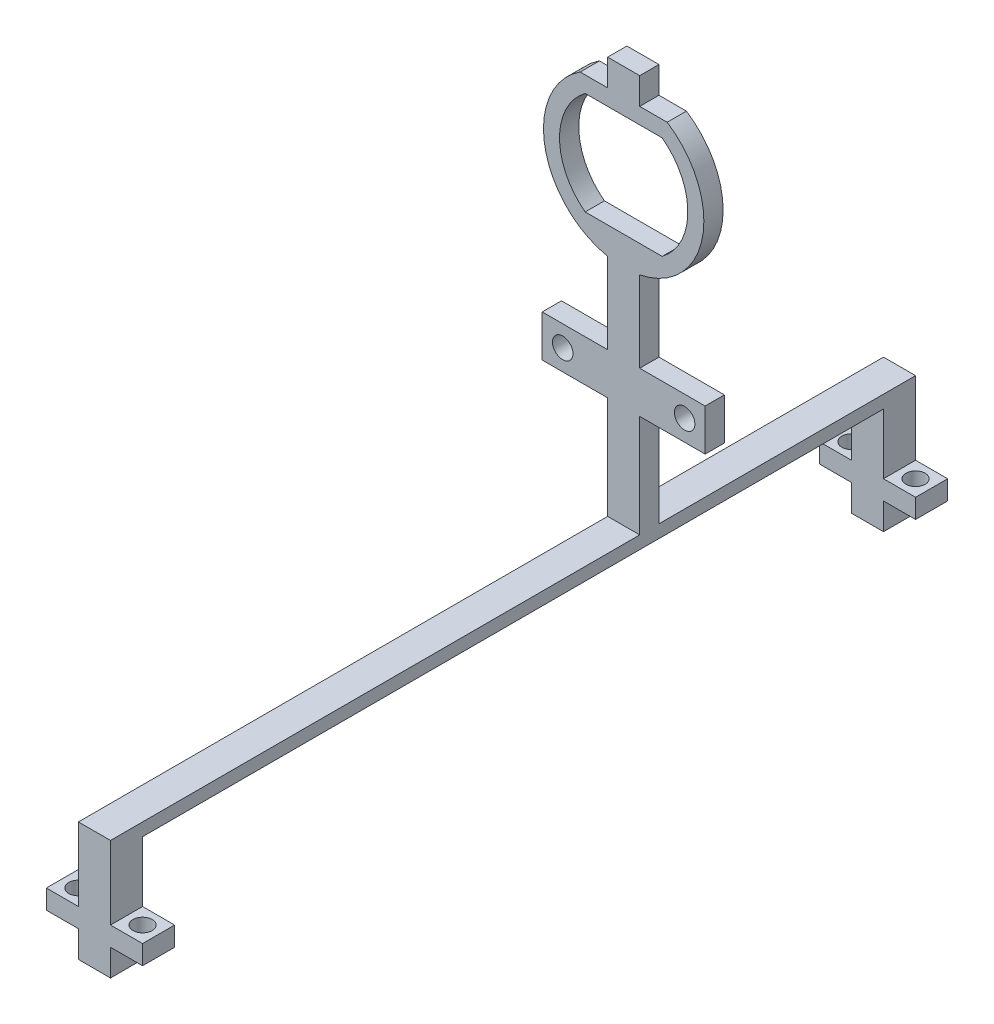
SolidWorks part; units mm, degrees
ref_plane "Front Plane" through (0, 0, 0) normal (0, 0, 1) x (1, 0, 0)
ref_plane "Top Plane" through (0, 0, 0) normal (0, 1, 0) x (1, 0, 0)
ref_plane "Right Plane" through (0, 0, 0) normal (1, 0, 0) x (0, 0, -1)
sketch "Sketch1" plane through (0, 0, 0) normal (0, 0, 1) x (1, 0, 0)
  line L5 (-18.4746, 0) -> (14.4817, 0) construction
  line L8 (0, 0) -> (0, 29.3453) construction
  line L13 (2.5, -49.3474) -> (2.5, -12.2474)
  line L18 (-2.5, -49.3474) -> (-2.5, -12.2474)
  line L21 (2.5, -49.3474) -> (-2.5, -49.3474)
  line L22 (6.7823, 10.5) -> (-6.7823, 10.5)
  line L24 (-6, -8) -> (6, -8)
  line L25 (-6, 8) -> (6, 8)
  arc A0 (-6, 8) -> (-6, -8) centre (0, 0) ccw
  arc A2 (-6.7823, 10.5) -> (-2.5, -12.2474) centre (0, 0) ccw
  arc A3 (2.5, -12.2474) -> (6.7823, 10.5) centre (0, 0) ccw
  arc A4 (6, -8) -> (6, 8) centre (0, 0) ccw
  dimension "D1" = 16
  dimension "D3" = 3.5
  dimension "D4" = 37.1
  dimension "D2" = 10
  dimension "D6" = 12.5
  dimension "D8" = 10
  dimension "D9" = 12.5
  dimension "D5" = 5
  dimension "D7" = 2.5
extrude "Boss-Extrude1" add sketch "Sketch1" along normal blind 3
sketch "Sketch3" plane through (0, 0, 0) normal (0, 0, 1) x (1, 0, 0)
  line L0 (0, -46.1586) -> (0, 0.6217) construction
  line L1 (12.7, -24.8474) -> (-12.7, -24.8474)
  line L2 (12.7, -24.8474) -> (12.7, -31.3474)
  line L3 (12.7, -31.3474) -> (-12.7, -31.3474)
  line L4 (-12.7, -24.8474) -> (-12.7, -31.3474)
  line L5 (12.7, -24.8474) -> (-12.7, -31.3474) construction
  line L6 (12.7, -31.3474) -> (-12.7, -24.8474) construction
  line L7 (2.5, -49.3474) -> (-2.5, -49.3474) construction
  circle A0 centre (-9.5, -28.0974) radius 1.6
  circle A1 centre (9.5, -28.0974) radius 1.6
  point P0 (0, -28.0974)
  dimension "D4" = 3.2
  dimension "D5" = 3.2
  dimension "D6" = 3.25
  dimension "D1" = 19
  dimension "D2" = 6.5
  dimension "D3" = 18
extrude "Boss-Extrude4" add sketch "Sketch3" along normal blind 3
sketch "Sketch11" plane through (0, 10.5, 0) normal (0, 1, 0) x (1, 0, 0)
  line L0 (6.7823, -3) -> (-6.7823, -3) construction
  line L1 (-2.5, 0) -> (2.5, 0)
  line L2 (-2.5, 0) -> (-2.5, -3)
  line L3 (-2.5, -3) -> (2.5, -3)
  line L4 (2.5, 0) -> (2.5, -3)
  line L5 (-2.5, 0) -> (2.5, -3) construction
  line L6 (-2.5, -3) -> (2.5, 0) construction
  line L11 (6.7823, 0) -> (-6.7823, 0) construction
  point P0 (0, -1.5)
  point P10 (0, 0)
  dimension "D1" = 3
  dimension "D2" = 5
extrude "Boss-Extrude8" add sketch "Sketch11" along normal blind 4.15
sketch "Sketch6" plane through (0, 0, 0) normal (0, 0, -1) x (-1, 0, 0)
  line L0 (2.5, -49.3474) -> (2.5, -31.3474) construction
  line L1 (-2.5, -49.3474) -> (2.5, -49.3474)
  line L2 (-2.5, -49.3474) -> (-2.5, -47.3474)
  line L3 (-2.5, -47.3474) -> (2.5, -47.3474)
  line L4 (2.5, -49.3474) -> (2.5, -47.3474)
  dimension "D1" = 2
extrude "Boss-Extrude5" add sketch "Sketch6" along normal blind 40
sketch "Sketch10" plane through (0, 0, 3) normal (0, 0, 1) x (1, 0, 0)
  line L0 (-2.5, -49.3474) -> (-2.5, -31.3474) construction
  line L1 (2.5, -49.3474) -> (-2.5, -49.3474)
  line L2 (2.5, -49.3474) -> (2.5, -47.3474)
  line L3 (2.5, -47.3474) -> (-2.5, -47.3474)
  line L4 (-2.5, -49.3474) -> (-2.5, -47.3474)
  dimension "D1" = 2
extrude "Boss-Extrude7" add sketch "Sketch10" along normal blind 82.49
sketch "Sketch14" plane through (0, 0, -40) normal (0, 0, -1) x (-1, 0, 0)
  line L0 (-2.5, -61.7674) -> (-2.5, -65.9174)
  line L5 (-2.5, -49.3474) -> (2.5, -49.3474)
  line L6 (-2.5, -49.3474) -> (-2.5, -58.7674)
  line L7 (-2.5, -65.9174) -> (2.5, -65.9174)
  line L8 (2.5, -49.3474) -> (2.5, -58.7674)
  line L9 (-7.5, -61.7674) -> (-2.5, -61.7674)
  line L10 (-7.5, -61.7674) -> (-7.5, -58.7674)
  line L11 (-7.5, -58.7674) -> (-2.5, -58.7674)
  line L12 (7.5, -61.7674) -> (7.5, -58.7674)
  line L13 (2.5, -61.7674) -> (2.5, -65.9174)
  line L14 (2.5, -58.7674) -> (7.5, -58.7674)
  line L15 (2.5, -61.7674) -> (7.5, -61.7674)
  dimension "D1" = 5
  dimension "D2" = 16.57
  dimension "D3" = 15
  dimension "D4" = 3
  dimension "D5" = 4.15
extrude "Boss-Extrude9" add sketch "Sketch14" against normal blind 5
sketch "Sketch15" plane through (0, -58.7674, 0) normal (0, 1, 0) x (1, 0, 0)
  line L0 (-7.5, 40) -> (-2.5, 40) construction
  line L1 (-7.5, 35) -> (-7.5, 40) construction
  circle A0 centre (-5, 37.5) radius 1.5
  dimension "D1" = 3
  dimension "D2" = 2.5
  dimension "D3" = 2.5
extrude "Cut-Extrude1" cut sketch "Sketch15" against normal blind 5
mirror "Mirror1" about plane through (0, 0, 0) normal (1, 0, 0) of "Cut-Extrude1"
ref_plane "Plane4" through (0, 0, 22.745) normal (0, 0, -1) x (-1, 0, 0)
mirror "Mirror2" about plane through (0, 0, 22.745) normal (0, 0, -1) of "Boss-Extrude9", "Cut-Extrude1", "Mirror1"
